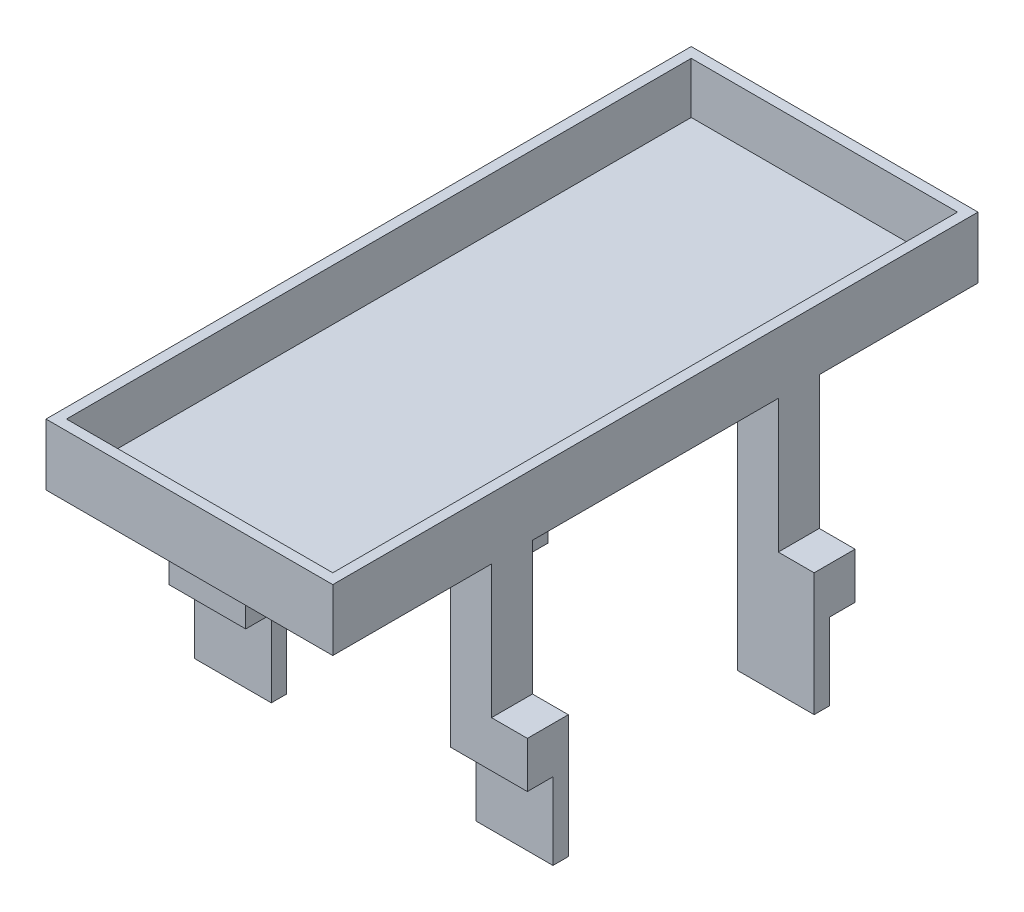
SolidWorks part; units mm, degrees
ref_plane "Front Plane" through (0, 0, 0) normal (0, 0, 1) x (1, 0, 0)
ref_plane "Top Plane" through (0, 0, 0) normal (0, 1, 0) x (1, 0, 0)
ref_plane "Right Plane" through (0, 0, 0) normal (1, 0, 0) x (0, 0, -1)
sketch "Sketch3" plane through (0, 0, 0) normal (1, 0, 0) x (0, 0, -1)
  line L0 (0, 0) -> (24, 0) construction
  line L1 (24, 0) -> (24, -50)
  line L2 (24, -50) -> (27, -50)
  line L3 (27, -50) -> (27, -35)
  line L4 (27, -35) -> (32, -35)
  line L5 (32, -35) -> (32, 0)
  line L6 (32, 0) -> (24, 0)
  line L7 (0, 0) -> (0, 14.7637) construction
  line L8 (-32, 0) -> (-24, 0)
  line L9 (-32, -35) -> (-32, 0)
  line L10 (-27, -35) -> (-32, -35)
  line L11 (-27, -50) -> (-27, -35)
  line L12 (-24, -50) -> (-27, -50)
  line L13 (-24, 0) -> (-24, -50)
  dimension "D1" = 35
  dimension "D2" = 15
  dimension "D3" = 3
  dimension "D4" = 5
  dimension "D5" = 24
extrude "Boss-Extrude1" add sketch "Sketch3" along normal mid plane 70
sketch "Sketch4" plane through (0, 0, 0) normal (0, 1, 0) x (1, 0, 0)
  line L1 (-28, 63) -> (28, 63)
  line L2 (-28, 63) -> (-28, -63)
  line L3 (-28, -63) -> (28, -63)
  line L4 (28, 63) -> (28, -63)
  line L5 (-28, 63) -> (28, -63) construction
  line L6 (-28, -63) -> (28, 63) construction
  point P0 (0, 0)
  dimension "D1" = 56
  dimension "D2" = 126
extrude "Boss-Extrude2" add sketch "Sketch4" along normal blind 12
sketch "Sketch5" plane through (0, 12, 0) normal (0, 1, 0) x (1, 0, 0)
  line L0 (28, -63) -> (28, 63) construction
  line L1 (-26, 61) -> (26, 61)
  line L2 (-26, 61) -> (-26, -61)
  line L3 (-26, -61) -> (26, -61)
  line L4 (26, 61) -> (26, -61)
  line L5 (-26, 61) -> (26, -61) construction
  line L6 (-26, -61) -> (26, 61) construction
  line L7 (28, 63) -> (-28, 63) construction
  point P0 (0, 0)
  dimension "D1" = 2
  dimension "D2" = 2
extrude "Cut-Extrude1" cut sketch "Sketch5" against normal blind 10
sketch "Sketch6" plane through (0, 0, 32) normal (0, 0, 1) x (1, 0, 0)
  line L0 (28, 0) -> (-28, 0) construction
  line L1 (-20, 0) -> (20, 0)
  line L2 (-20, 0) -> (-20, -50)
  line L3 (-20, -50) -> (20, -50)
  line L4 (20, 0) -> (20, -50)
  line L5 (35, -50) -> (-35, -50) construction
  line L6 (0, 0) -> (0, -24.7525) construction
  line L7 (-35, 0) -> (-28, 0)
  line L8 (-35, 0) -> (-35, -26)
  line L9 (-35, -26) -> (-28, -26)
  line L10 (-28, 0) -> (-28, -26)
  line L11 (35, -26) -> (28, -26)
  line L12 (28, 0) -> (28, -26)
  line L13 (35, 0) -> (28, 0)
  line L14 (35, 0) -> (35, -26)
  line L15 (-28, 12) -> (-28, 0) construction
  dimension "D1" = 40
  dimension "D3" = 26
extrude "Cut-Extrude2" cut sketch "Sketch6" against normal through all and the other way through all
